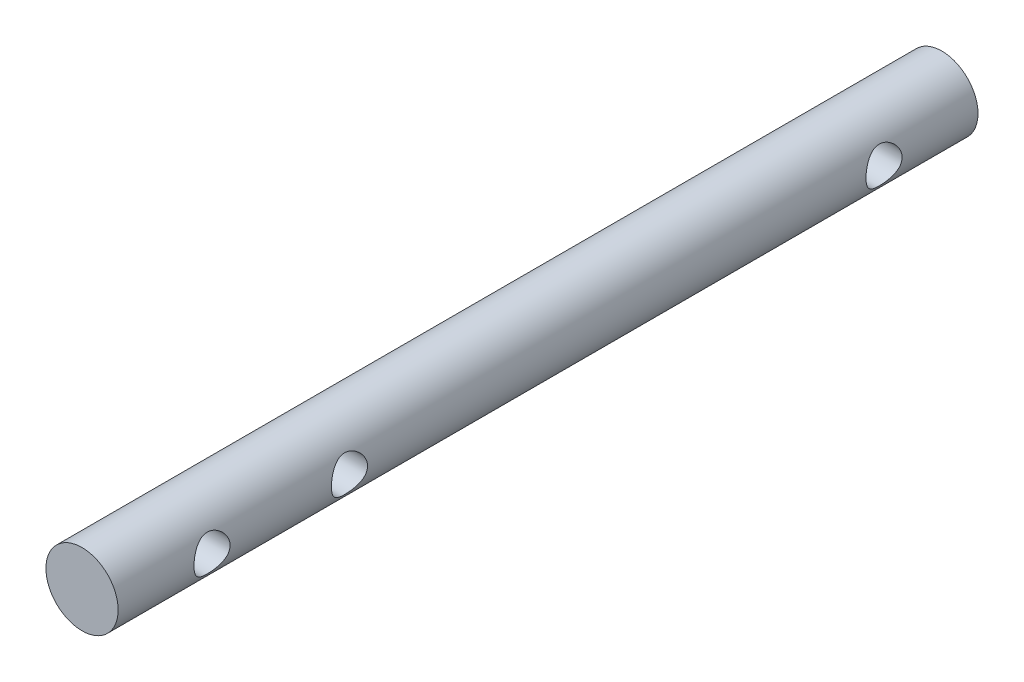
SolidWorks part; units mm, degrees
ref_plane "Front Plane" through (0, 0, 0) normal (0, 0, 1) x (1, 0, 0)
ref_plane "Top Plane" through (0, 0, 0) normal (0, 1, 0) x (1, 0, 0)
ref_plane "Right Plane" through (0, 0, 0) normal (1, 0, 0) x (0, 0, -1)
sketch "Sketch2" plane through (0, 0, 0) normal (0, 0, 1) x (1, 0, 0)
  circle A0 centre (0, 0) radius 4.995
  dimension "D1" = 9.99
extrude "Boss-Extrude1" add sketch "Sketch2" along normal blind 119
ref_plane "Plane1" through (-4.995, 0, 0) normal (-1, 0, 0) x (0, 0, 1)
sketch "Sketch5" plane through (-4.995, 0, 0) normal (-1, 0, 0) x (0, 0, 1)
  line L0 (0, 0) -> (13, 0)
  line L1 (55, 0) -> (-55, 0) construction
  dimension "D1" = 13
hole_wizard "Ø5.0mm Dowel Hole1" positions "Sketch7" profile "Sketch8" hole size "Ø5.0" standard "ANSI Metric" end condition through all
sketch "Sketch7" plane through (-4.995, 0, 0) normal (-1, 0, 0) x (0, 0, 1)
  line L0 (0, 4.995) -> (0, -4.995) construction
  point P0 (13, 0)
  dimension "D1" = 13
sketch "Sketch8" plane through (-4.995, 0, 13) normal (0, 1, 0) x (0, 0, 1)
  line L0 (0, 0) -> (0, 9.99)
  line L1 (0, 9.99) -> (2.5, 9.99)
  line L2 (2.5, 9.99) -> (2.5, 0.025)
  line L3 (2.5, 0.025) -> (2.525, 0)
  line L5 (2.525, 0) -> (0, 0)
  line L6 (-2.5, 0.025) -> (-2.525, 0) construction
  line L11 (0, -6.35) -> (0, 107.95) construction
  dimension "Thru Hole Dia." = 5
  dimension "Thru Hole Depth" = 9.99
  dimension "Near C'Sink Dia." = 5.05
  dimension "Near C'Sink Angle" = 90
ref_plane "Plane2" through (0, 0, 59.5) normal (0, 0, -1) x (-1, 0, 0)
mirror "Mirror1" about plane through (0, 0, 59.5) normal (0, 0, -1) of "Ø5.0mm Dowel Hole1"
sketch "Sketch9" plane through (-4.995, 0, 0) normal (-1, 0, 0) x (0, 0, 1)
  line L0 (0, 0) -> (86.98, 0)
  line L1 (0, 4.995) -> (0, -4.995) construction
  line L2 (86.98, 0) -> (119, 0)
  line L3 (119, -4.995) -> (119, 4.995) construction
  dimension "D1" = 32.02
hole_wizard "Ø5.0mm Dowel Hole2" positions "Sketch10" profile "Sketch11" hole size "Ø5.0" standard "ANSI Metric" end condition through all
sketch "Sketch10" plane through (-4.995, 0, 0) normal (-1, 0, 0) x (0, 0, 1)
  point P0 (86.98, 0)
sketch "Sketch11" plane through (-4.995, 0, 86.98) normal (0, 1, 0) x (0, 0, 1)
  line L0 (0, 0) -> (0, 9.99)
  line L1 (0, 9.99) -> (2.5, 9.99)
  line L2 (2.5, 9.99) -> (2.5, 0.025)
  line L3 (2.5, 0.025) -> (2.525, 0)
  line L5 (2.525, 0) -> (0, 0)
  line L6 (-2.5, 0.025) -> (-2.525, 0) construction
  line L11 (0, -6.35) -> (0, 107.95) construction
  dimension "Thru Hole Dia." = 5
  dimension "Thru Hole Depth" = 9.99
  dimension "Near C'Sink Dia." = 5.05
  dimension "Near C'Sink Angle" = 90
